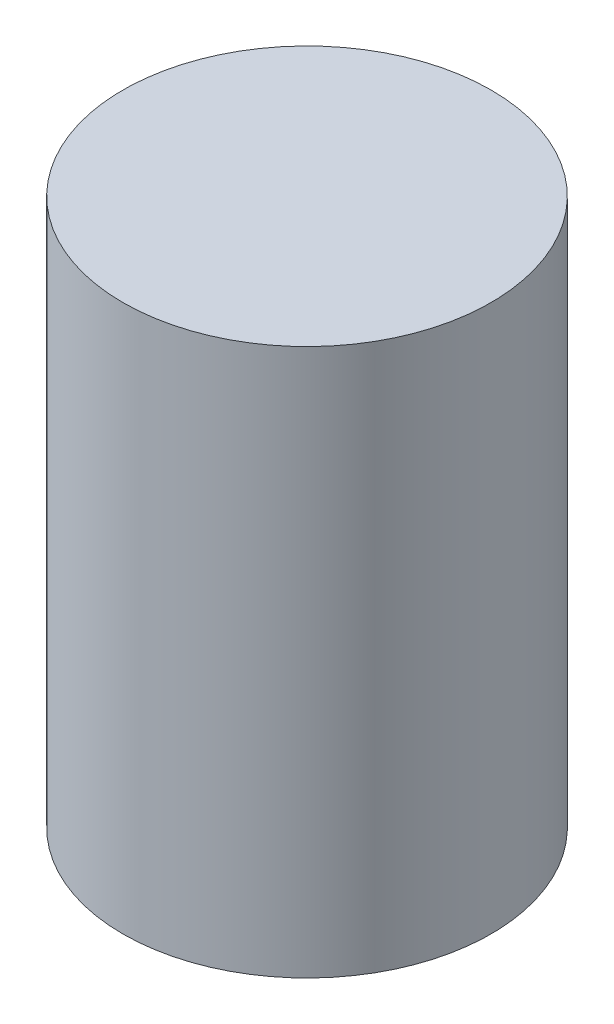
SolidWorks part; units mm, degrees
ref_plane "Front Plane" through (0, 0, 0) normal (0, 0, 1) x (1, 0, 0)
ref_plane "Top Plane" through (0, 0, 0) normal (0, 1, 0) x (1, 0, 0)
ref_plane "Right Plane" through (0, 0, 0) normal (1, 0, 0) x (0, 0, -1)
sketch "Sketch1" plane through (0, 0, 0) normal (0, 1, 0) x (1, 0, 0)
  circle A0 centre (0, 0) radius 6.8
  dimension "D1" = 13.6
extrude "Boss-Extrude1" add sketch "Sketch1" along normal blind 20.2
